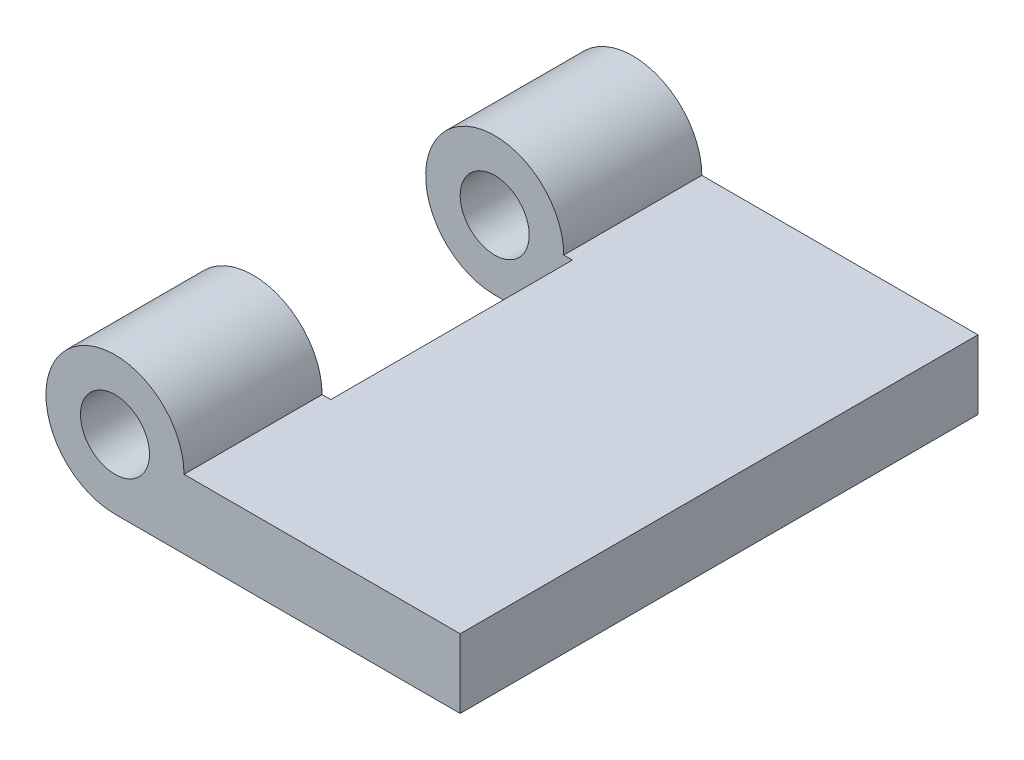
SolidWorks part; units mm, degrees
ref_plane "前视基准面" through (0, 0, 0) normal (0, 0, 1) x (1, 0, 0)
ref_plane "上视基准面" through (0, 0, 0) normal (0, 1, 0) x (1, 0, 0)
ref_plane "右视基准面" through (0, 0, 0) normal (1, 0, 0) x (0, 0, -1)
sketch "草图1" plane through (0, 0, 0) normal (0, 0, 1) x (1, 0, 0)
  line L1 (4, 0) -> (20, 0)
  line L3 (0, -4) -> (20, -4)
  line L4 (20, 0) -> (20, -4)
  arc A0 (4, 0) -> (0, -4) centre (0, 0) ccw
  dimension "D1" = 20
  dimension "D2" = 4
extrude "凸台-拉伸1" add sketch "草图1" along normal blind 30
sketch "草图2" plane through (0, -4, 0) normal (0, -1, 0) x (1, 0, 0)
  line L0 (0, 30) -> (0, 0) construction
  line L1 (-4.5, 8) -> (4.5, 8)
  line L2 (-4.5, 8) -> (-4.5, 22)
  line L3 (-4.5, 22) -> (4.5, 22)
  line L4 (4.5, 8) -> (4.5, 22)
  line L5 (-4.5, 8) -> (4.5, 22) construction
  line L6 (-4.5, 22) -> (4.5, 8) construction
  line L7 (4, 30) -> (-4, 30) construction
  point P0 (0, 15)
  point P5 (0, 15.6732)
  dimension "D1" = 14
  dimension "D2" = 9
  dimension "D3" = 15
extrude "切除-拉伸1" cut sketch "草图2" against normal blind 15
sketch "草图3" plane through (0, 0, 0) normal (0, 0, -1) x (-1, 0, 0)
  circle A0 centre (0, 0) radius 2
extrude "切除-拉伸2" cut sketch "草图3" against normal blind 32
